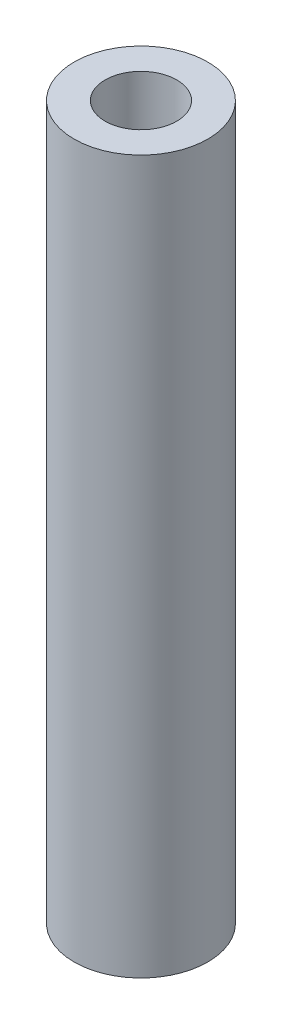
SolidWorks part; units mm, degrees
ref_plane "Front Plane" through (0, 0, 0) normal (0, 0, 1) x (1, 0, 0)
ref_plane "Top Plane" through (0, 0, 0) normal (0, 1, 0) x (1, 0, 0)
ref_plane "Right Plane" through (0, 0, 0) normal (1, 0, 0) x (0, 0, -1)
sketch "Sketch1" plane through (0, 0, 0) normal (0, 1, 0) x (1, 0, 0)
  circle A0 centre (0, 0) radius 2.5527
  circle A1 centre (0, 0) radius 4.7625
  dimension "D1" = 5.1054
  dimension "D2" = 9.525
extrude "Boss-Extrude1" add sketch "Sketch1" along normal mid plane 50.8
